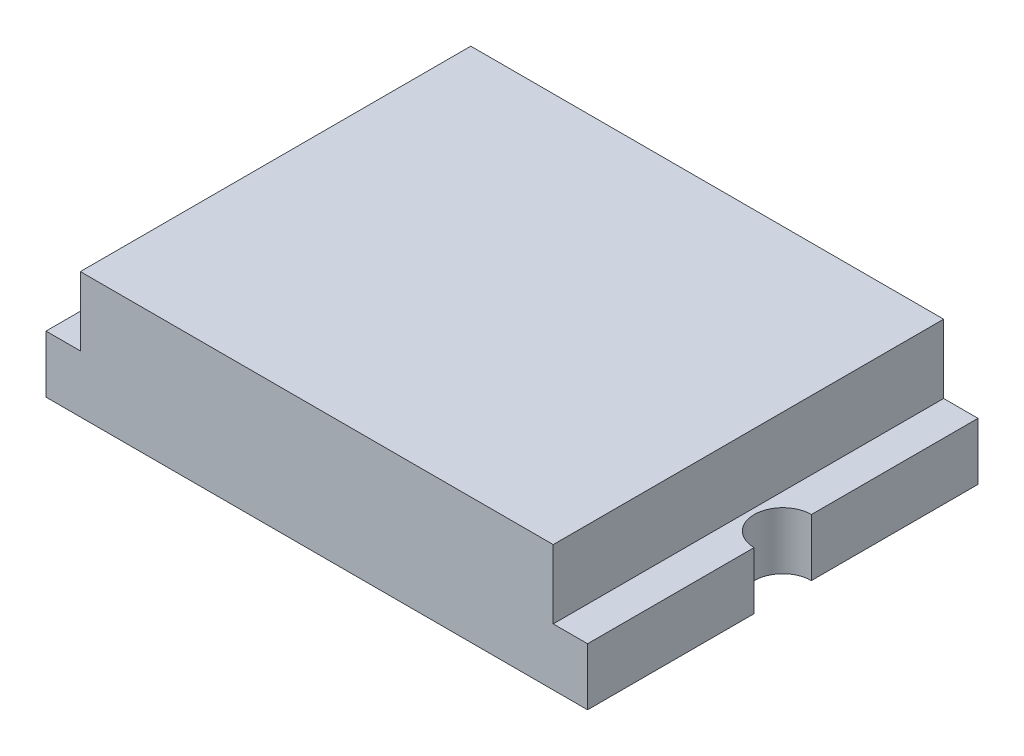
SolidWorks part; units mm, degrees
ref_plane "前视基准面" through (0, 0, 0) normal (0, 0, 1) x (1, 0, 0)
ref_plane "上视基准面" through (0, 0, 0) normal (0, 1, 0) x (1, 0, 0)
ref_plane "右视基准面" through (0, 0, 0) normal (1, 0, 0) x (0, 0, -1)
sketch "草图1" plane through (0, 0, 0) normal (0, 1, 0) x (1, 0, 0)
  line L0 (-2.365, 0) -> (2.365, 0) construction
  line L1 (-2.365, -1.705) -> (-2.065, -1.705)
  line L2 (-2.365, -1.705) -> (-2.365, -0.25)
  line L3 (-2.365, 1.705) -> (-2.065, 1.705)
  line L4 (2.365, -1.705) -> (2.365, -0.25)
  line L5 (-2.365, -1.705) -> (2.365, 1.705) construction
  line L6 (-2.365, 1.705) -> (2.365, -1.705) construction
  line L7 (2.065, 1.705) -> (2.365, 1.705)
  line L9 (-2.065, -1.705) -> (-2.065, 1.705)
  line L11 (2.065, -1.705) -> (2.065, 1.705)
  line L12 (-2.065, -1.705) -> (2.065, 1.705) construction
  line L13 (-2.065, 1.705) -> (2.065, -1.705) construction
  line L14 (2.065, -1.705) -> (2.365, -1.705)
  line L15 (-2.365, 0.25) -> (-2.365, 1.705)
  line L16 (2.365, 0.25) -> (2.365, 1.705)
  arc A0 (-2.365, -0.25) -> (-2.365, 0.25) centre (-2.365, 0) ccw
  arc A1 (2.365, 0.25) -> (2.365, -0.25) centre (2.365, 0) ccw
  point P0 (0, 0)
  point P10 (0, 0)
  dimension "D3" = 0.5
  dimension "D4" = 0.5
  dimension "D1" = 4.73
  dimension "D2" = 3.41
  dimension "D5" = 4.13
extrude "凸台-拉伸1" add sketch "草图1" along normal blind 0.5
sketch "草图2" plane through (0, 0, 0) normal (0, 1, 0) x (1, 0, 0)
  line L1 (-2.065, 1.705) -> (2.065, 1.705)
  line L2 (-2.065, 1.705) -> (-2.065, -1.705)
  line L3 (-2.065, -1.705) -> (2.065, -1.705)
  line L4 (2.065, 1.705) -> (2.065, -1.705)
  line L5 (-2.065, 1.705) -> (2.065, -1.705) construction
  line L6 (-2.065, -1.705) -> (2.065, 1.705) construction
  point P0 (0, 0)
extrude "凸台-拉伸2" add sketch "草图2" along normal blind 1.1
